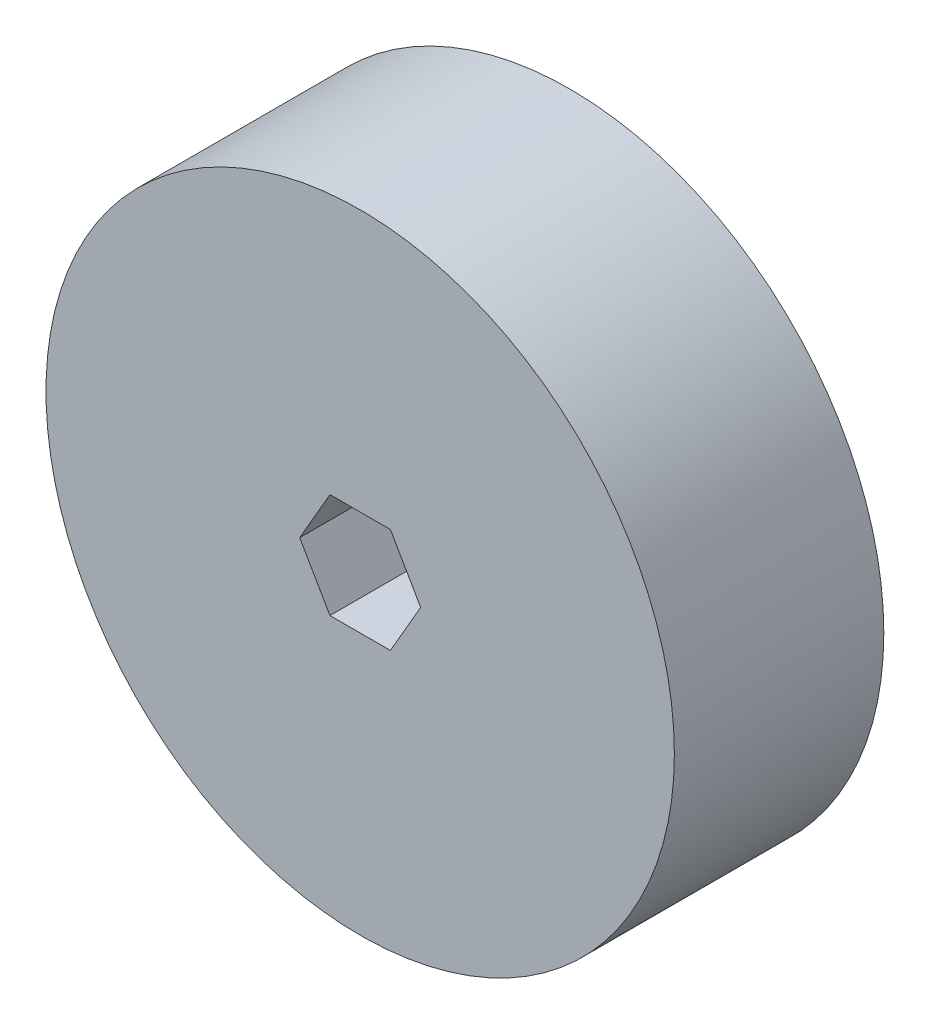
SolidWorks part; units mm, degrees
ref_plane "Front Plane" through (0, 0, 0) normal (0, 0, 1) x (1, 0, 0)
ref_plane "Top Plane" through (0, 0, 0) normal (0, 1, 0) x (1, 0, 0)
ref_plane "Right Plane" through (0, 0, 0) normal (1, 0, 0) x (0, 0, -1)
sketch "Sketch1" plane through (0, 0, 0) normal (0, 0, 1) x (1, 0, 0)
  line L1 (-3.6662, 6.35) -> (-7.3323, 0)
  line L2 (-7.3323, 0) -> (-3.6662, -6.35)
  line L3 (-3.6662, -6.35) -> (3.6662, -6.35)
  line L4 (3.6662, -6.35) -> (7.3323, 0)
  line L5 (7.3323, 0) -> (3.6662, 6.35)
  line L6 (3.6662, 6.35) -> (-3.6662, 6.35)
  circle A0 centre (0, 0) radius 38.1
  circle A1 centre (0, 0) radius 6.35 construction
  dimension "D1" = 76.2
  dimension "D2" = 12.7
extrude "Boss-Extrude1" add sketch "Sketch1" along normal blind 25.4
